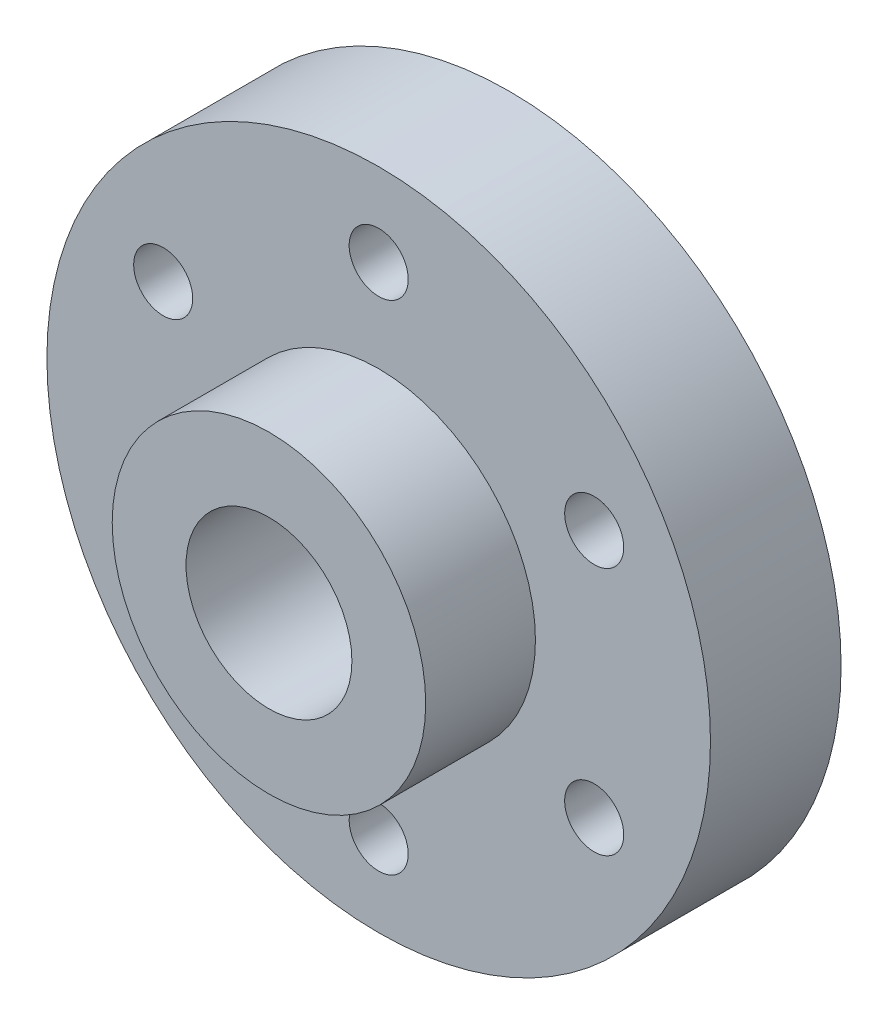
SolidWorks part; units mm, degrees
ref_plane "Front Plane" through (0, 0, 0) normal (0, 0, 1) x (1, 0, 0)
ref_plane "Top Plane" through (0, 0, 0) normal (0, 1, 0) x (1, 0, 0)
ref_plane "Right Plane" through (0, 0, 0) normal (1, 0, 0) x (0, 0, -1)
sketch "Sketch2" plane through (0, 0, 0) normal (0, 0, 1) x (1, 0, 0)
  circle A0 centre (0, 0) radius 12.7
  circle A1 centre (0, 0) radius 3.175
  dimension "D1" = 25.4
  dimension "D2" = 6.35
extrude "Boss-Extrude1" add sketch "Sketch2" along normal blind 5
sketch "Sketch3" plane through (0, 0, 5) normal (0, 0, 1) x (1, 0, 0)
  circle A0 centre (0, 0) radius 6
  circle A1 centre (0, 0) radius 3.175
  dimension "D1" = 12
  dimension "D2" = 6.35
extrude "Boss-Extrude2" add sketch "Sketch3" along normal blind 4.2
sketch "Sketch4" plane through (0, 0, 5) normal (0, 0, 1) x (1, 0, 0)
  line L0 (0, 0) -> (0, 9.525) construction
  circle A0 centre (0, 9.525) radius 1.1303
  dimension "D1" = 2.2606
  dimension "D2" = 9.525
extrude "Cut-Extrude1" cut sketch "Sketch4" against normal up to next
pattern_circular "CirPattern1" count 6 over 360 about axis through (0, 0, 0) along (0, 0, 1) of "Cut-Extrude1"
